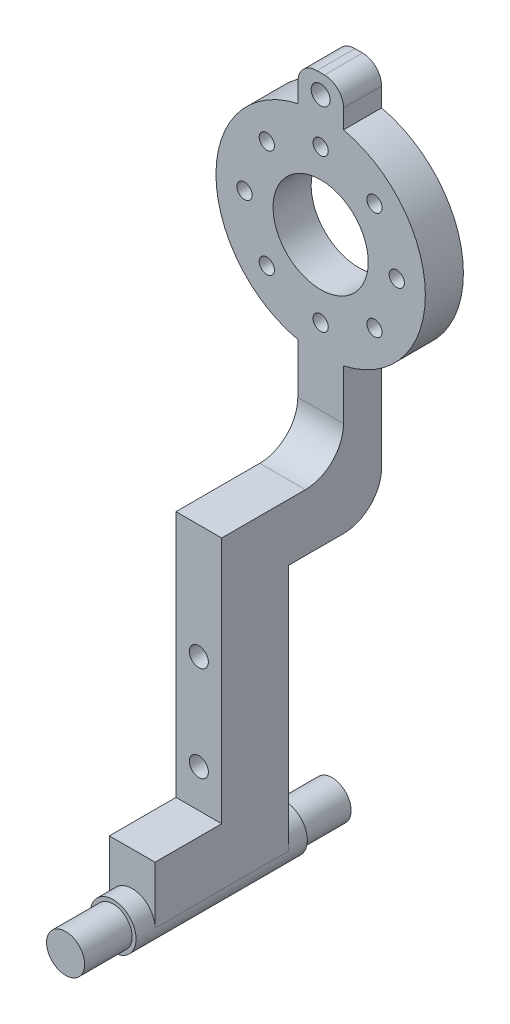
SolidWorks part; units mm, degrees
ref_plane "前视基准面" through (0, 0, 0) normal (0, 0, 1) x (1, 0, 0)
ref_plane "上视基准面" through (0, 0, 0) normal (0, 1, 0) x (1, 0, 0)
ref_plane "右视基准面" through (0, 0, 0) normal (1, 0, 0) x (0, 0, -1)
sketch "草图1" plane through (0, 0, 0) normal (0, 0, 1) x (1, 0, 0)
  circle A0 centre (0, 0) radius 5
  dimension "D1" = 10
extrude "凸台-拉伸1" add sketch "草图1" along normal blind 12.5 contours A0
sketch "草图2" plane through (0, 0, 12.5) normal (0, 0, 1) x (1, 0, 0)
  circle A0 centre (0, 0) radius 6
  dimension "D1" = 12
extrude "凸台-拉伸2" add sketch "草图2" along normal blind 22.5
mirror "镜向2" about plane through (0, 0, 35) normal (0, 0, 1) of "凸台-拉伸2"
sketch "草图3" plane through (0, 0, 57.5) normal (0, 0, 1) x (1, 0, 0)
  circle A0 centre (0, 0) radius 5
  dimension "D1" = 10
extrude "凸台-拉伸3" add sketch "草图3" along normal blind 12.5
sketch "草图4" plane through (0, 0, 0) normal (0, 1, 0) x (1, 0, 0)
  line L0 (-5, -57.5) -> (5, -57.5) construction
  line L1 (6, -12.5) -> (-6, -12.5) construction
  line L2 (6, -57.5) -> (6, -12.5) construction
  line L3 (-6, -12.5) -> (-6, -57.5) construction
  line L4 (-6, -57.5) -> (6, -57.5)
  line L5 (6, -12.5) -> (-6, -12.5)
  line L6 (6, -57.5) -> (6, -12.5)
  line L7 (-6, -12.5) -> (-6, -57.5)
  line L8 (-6, -17.5) -> (6, -17.5)
  line L9 (-6, -52.5) -> (6, -52.5)
  dimension "D1" = 5
  dimension "D2" = 5
extrude "凸台-拉伸4" add sketch "草图4" along normal blind 80 contours L7 L9 L6 L8
sketch "草图5" plane through (-6, 0, 0) normal (-1, 0, 0) x (0, 0, 1)
  line L0 (17.5, 130) -> (52.5, 130) construction
  line L1 (35, 50) -> (35, 100) construction
  line L2 (35, 80) -> (13, 80)
  line L3 (3, 90) -> (3, 130)
  line L4 (17.5, 0) -> (52.5, 0)
  line L5 (52.5, 0) -> (52.5, 80)
  line L6 (52.5, 80) -> (17.5, 80)
  line L7 (17.5, 80) -> (17.5, 0)
  line L8 (17.5, 0) -> (52.5, 0)
  line L9 (52.5, 0) -> (52.5, 80)
  line L10 (52.5, 80) -> (17.5, 80)
  line L11 (17.5, 80) -> (17.5, 0)
  line L12 (3, 130) -> (-7, 130)
  line L13 (-7, 130) -> (-7, 75)
  line L14 (3, 65) -> (17.5, 65)
  line L15 (52.5, 80) -> (59, 80)
  line L16 (69, 90) -> (69, 130)
  line L17 (69, 130) -> (79, 130)
  line L18 (79, 130) -> (79, 75)
  line L19 (69, 65) -> (52.5, 65)
  arc A0 (13, 80) -> (3, 90) centre (13, 90) cw
  arc A1 (3, 65) -> (-7, 75) centre (3, 75) cw
  arc A2 (79, 75) -> (69, 65) centre (69, 75) cw
  arc A3 (69, 90) -> (59, 80) centre (59, 90) cw
  point P16 (3, 80)
  point P28 (69, 80)
  line M10 (17.5, 80) -> (17.5, 0)
  dimension "D6" = 10
  dimension "D7" = 10
  dimension "D11" = 10
  dimension "D2" = 50
  dimension "D3" = 32
  dimension "D4" = 10
  dimension "D5" = 15
  dimension "D8" = 34
  dimension "D9" = 10
  dimension "D10" = 15
  dimension "D1" = 0
extrude "凸台-拉伸5" add sketch "草图5" against normal up to surface (12 mm away) contours A1 L14 L2 A0 L3 L12 L13 M10 | L16 A3 L15 L9 L19 A2 L18 L17 up to face at (6, 40, 35)
sketch "草图6" plane through (0, 0, 69) normal (0, 0, -1) x (-1, 0, 0)
  line L4 (6, 130) -> (-6, 130)
  line L5 (-6, 130) -> (-6, 90)
  line L6 (-6, 90) -> (6, 90)
  line L7 (6, 90) -> (6, 130)
  line L8 (6, 130) -> (-6, 130)
  line L9 (-6, 130) -> (-6, 90)
  line L10 (-6, 90) -> (6, 90)
  line L11 (6, 90) -> (6, 130)
  circle A2 centre (0, 130) radius 15
  line M7 (6, 130) -> (-6, 130)
  line M8 (-6, 130) -> (-6, 90)
  dimension "D3" = 30
  dimension "D1" = 0
extrude "凸台-拉伸6" add sketch "草图6" against normal up to surface (10 mm away) contours L11 A2 M8 M7 up to face at (0, 102.5, 79)
sketch "草图7" plane through (0, 0, 69) normal (0, 0, -1) x (-1, 0, 0)
  arc A0 (6, 116.2523) -> (-6, 116.2523) centre (0, 130) ccw construction
  arc A1 (6, 116.2523) -> (-6, 116.2523) centre (0, 130) ccw
  circle A2 centre (0, 130) radius 9.5
  dimension "D1" = 19
extrude "切除-拉伸1" cut sketch "草图7" against normal blind 2 contours A2
sketch "草图8" plane through (0, 0, 71) normal (0, 0, -1) x (-1, 0, 0)
  circle A0 centre (0, 130) radius 6
  circle A1 centre (0, 130) radius 9.5
  circle A2 centre (0, 130) radius 9.5
  dimension "D2" = 12
  dimension "D1" = 0
extrude "切除-拉伸2" cut sketch "草图8" against normal through all contours A0
sketch "草图9" plane through (0, 0, 79) normal (0, 0, 1) x (1, 0, 0)
  line L0 (-15, 130) -> (-15, 155)
  line L1 (-15, 155) -> (15, 155)
  line L2 (15, 155) -> (15, 130)
  line L3 (-6, 116.2523) -> (-6, 75)
  line L4 (-6, 75) -> (6, 75)
  line L5 (6, 75) -> (6, 116.2523)
  line L6 (-6, 116.2523) -> (-6, 75)
  line L7 (-6, 75) -> (6, 75)
  line L8 (6, 75) -> (6, 116.2523)
  arc A1 (6, 116.2523) -> (-6, 116.2523) centre (0, 130) ccw
  arc A2 (6, 116.2523) -> (-6, 116.2523) centre (0, 130) ccw
  arc M7 (6, 116.2523) -> (-6, 116.2523) centre (0, 130) ccw
  dimension "D2" = 25
  dimension "D1" = 0
extrude "凸台-拉伸7" add sketch "草图9" against normal up to surface (10 mm away) contours L2 L1 L0 M7 up to face at (-9.5, 130, 69)
sketch "草图10" plane through (0, 0, 79) normal (0, 0, 1) x (1, 0, 0)
  line L6 (15, 130) -> (15, 155)
  line L7 (15, 155) -> (-15, 155)
  line L8 (-15, 155) -> (-15, 130)
  line L9 (-6, 116.2523) -> (-6, 75)
  line L10 (-6, 75) -> (6, 75)
  line L11 (6, 75) -> (6, 116.2523)
  line L12 (15, 130) -> (15, 155)
  line L13 (15, 155) -> (-15, 155)
  line L14 (-15, 155) -> (-15, 130)
  line L15 (-6, 116.2523) -> (-6, 75)
  line L16 (-6, 75) -> (6, 75)
  line L17 (6, 75) -> (6, 116.2523)
  circle A0 centre (10, 150) radius 2.5
  arc A2 (6, 116.2523) -> (15, 130) centre (0, 130) ccw
  arc A3 (-15, 130) -> (-6, 116.2523) centre (0, 130) ccw
  arc A4 (6, 116.2523) -> (15, 130) centre (0, 130) ccw
  arc A5 (-15, 130) -> (-6, 116.2523) centre (0, 130) ccw
  dimension "D4" = 5
  dimension "D2" = 5
  dimension "D3" = 5
  dimension "D1" = 0
extrude "切除-拉伸3" cut sketch "草图10" against normal up to surface (10 mm away) contours A0 up to face at (-9.5, 130, 69)
fillet "圆角1" radius 5 1 edges at (15, 155, 74)
fillet "圆角2" radius 5 1 edges at (-15, 155, 74)
sketch "草图11" plane through (0, 0, 79) normal (0, 0, 1) x (1, 0, 0)
  line L6 (10, 155) -> (-10, 155)
  line L7 (-15, 150) -> (-15, 130)
  line L8 (-6, 116.2523) -> (-6, 75)
  line L9 (-6, 75) -> (6, 75)
  line L10 (6, 75) -> (6, 116.2523)
  line L11 (15, 130) -> (15, 150)
  line L12 (10, 155) -> (-10, 155)
  line L13 (-15, 150) -> (-15, 130)
  line L14 (-6, 116.2523) -> (-6, 75)
  line L15 (-6, 75) -> (6, 75)
  line L16 (6, 75) -> (6, 116.2523)
  line L17 (15, 130) -> (15, 150)
  circle A0 centre (-10, 150) radius 2.5
  arc A4 (-10, 155) -> (-15, 150) centre (-10, 150) ccw
  arc A5 (-15, 130) -> (-6, 116.2523) centre (0, 130) ccw
  arc A6 (6, 116.2523) -> (15, 130) centre (0, 130) ccw
  arc A7 (15, 150) -> (10, 155) centre (10, 150) ccw
  arc A8 (-10, 155) -> (-15, 150) centre (-10, 150) ccw
  arc A9 (-15, 130) -> (-6, 116.2523) centre (0, 130) ccw
  arc A10 (6, 116.2523) -> (15, 130) centre (0, 130) ccw
  arc A11 (15, 150) -> (10, 155) centre (10, 150) ccw
  dimension "D2" = 5
  dimension "D1" = 0
extrude "切除-拉伸4" cut sketch "草图11" against normal up to surface (10 mm away) contours A0 up to face at (12.5, 150, 69)
sketch "草图12" plane through (0, 0, 3) normal (0, 0, 1) x (1, 0, 0)
  line L4 (6, 90) -> (6, 130)
  line L5 (6, 130) -> (-6, 130)
  line L6 (-6, 130) -> (-6, 90)
  line L7 (-6, 90) -> (6, 90)
  line L8 (6, 90) -> (6, 130)
  line L9 (6, 130) -> (-6, 130)
  line L10 (-6, 130) -> (-6, 90)
  line L11 (-6, 90) -> (6, 90)
  circle A0 centre (0, 130) radius 27.5
  line M6 (6, 130) -> (-6, 130)
  line M7 (-6, 130) -> (-6, 90)
  dimension "D2" = 55
  dimension "D1" = 0
extrude "凸台-拉伸8" add sketch "草图12" against normal up to surface (10 mm away) contours L8 A0 M7 M6 up to face at (0, 102.5, -7)
sketch "草图13" plane through (0, 0, -7) normal (0, 0, -1) x (-1, 0, 0)
  line L3 (6, 75) -> (6, 103.1625)
  line L4 (-6, 103.1625) -> (-6, 75)
  line L5 (-6, 75) -> (6, 75)
  line L6 (6, 75) -> (6, 103.1625)
  line L7 (-6, 103.1625) -> (-6, 75)
  line L8 (-6, 75) -> (6, 75)
  circle A0 centre (0, 130) radius 20 construction
  arc A1 (6, 103.1625) -> (-6, 103.1625) centre (0, 130) ccw
  arc A2 (6, 103.1625) -> (-6, 103.1625) centre (0, 130) ccw
  circle A3 centre (0, 150) radius 2
  circle A4 centre (0, 130) radius 12.5
  dimension "D2" = 40
  dimension "D3" = 4
  dimension "D4" = 25
  dimension "D1" = 0
extrude "切除-拉伸5" cut sketch "草图13" against normal up to surface (10 mm away) contours A4 | A3 up to face at (0, 110.1656, 3)
pattern_circular "阵列(圆周)1" count 8 over 360 about axis through (0, 130, 0) along (0, 0, 1) of "切除-拉伸5"
sketch "草图14" plane through (0, 0, -7) normal (0, 0, -1) x (-1, 0, 0)
  line L0 (-6, 156.8375) -> (-6, 161.8375)
  line L1 (-1, 166.8375) -> (1, 166.8375)
  line L2 (6, 161.8375) -> (6, 156.8375)
  line L3 (6, 75) -> (6, 103.1625)
  line L4 (-6, 103.1625) -> (-6, 75)
  line L5 (-6, 75) -> (6, 75)
  line L6 (6, 75) -> (6, 103.1625)
  line L7 (-6, 103.1625) -> (-6, 75)
  line L8 (-6, 75) -> (6, 75)
  circle A0 centre (0, 161.8375) radius 2.5
  arc A1 (6, 103.1625) -> (-6, 103.1625) centre (0, 130) ccw
  arc A2 (6, 103.1625) -> (-6, 103.1625) centre (0, 130) ccw
  arc A3 (6, 161.8375) -> (1, 166.8375) centre (1, 161.8375) ccw
  arc A4 (-1, 166.8375) -> (-6, 161.8375) centre (-1, 161.8375) ccw
  point P13 (6, 166.8375)
  point P16 (-6, 166.8375)
  arc M17 (6, 103.1625) -> (-6, 103.1625) centre (0, 130) ccw
  dimension "D4" = 5
  dimension "D6" = 5
  dimension "D2" = 12
  dimension "D3" = 10
  dimension "D5" = 5
  dimension "D1" = 0
extrude "凸台-拉伸9" add sketch "草图14" against normal up to surface (10 mm away) contours L1 A4 L0 L2 A3 A0 M17 up to face at (-12.1421, 115.8579, 3)
sketch "草图15" plane through (0, 0, 17.5) normal (0, 0, -1) x (-1, 0, 0)
  line L3 (6, 65) -> (-6, 65)
  line L4 (-6, 65) -> (-6, 0)
  line L5 (6, 0) -> (6, 65)
  line L6 (6, 65) -> (-6, 65)
  line L7 (-6, 65) -> (-6, 0)
  line L8 (6, 0) -> (6, 65)
  circle A0 centre (0, 25) radius 2.5
  arc A1 (6, 0) -> (-6, 0) centre (0, 0) ccw
  arc A2 (6, 0) -> (-6, 0) centre (0, 0) ccw
  circle A3 centre (0, 50) radius 2.5
  dimension "D4" = 6
  dimension "D5" = 5
  dimension "D6" = 5
  dimension "D2" = 25
  dimension "D3" = 15
  dimension "D1" = 0
extrude "切除-拉伸6" cut sketch "草图15" against normal up to surface (35 mm away) contours A0 | A3 up to face at (0, 34, 52.5)
ref_plane "基准面1" through (0, 0, 35) normal (0, 0, 1) x (1, 0, 0)
sketch "草图16" plane through (0, 0, 35) normal (0, 0, 1) x (1, 0, 0)
  line L0 (-6, 65) -> (-6, 0) construction
  line L1 (6, 65) -> (6, 0) construction
  line L2 (-6, 65) -> (-6, 0)
  line L3 (6, 65) -> (6, 0)
  line L4 (6, 65) -> (6, 97.6533)
  line L5 (6, 97.6533) -> (-6, 97.6533)
  line L6 (-6, 97.6533) -> (-6, 65)
  line L7 (6, 0) -> (-6, 0)
  line L8 (6, 15) -> (-6, 15)
  dimension "D1" = 15
extrude "切除-拉伸7" cut sketch "草图16" along normal through all contours L8 L3 L4 L5 L6 L2
